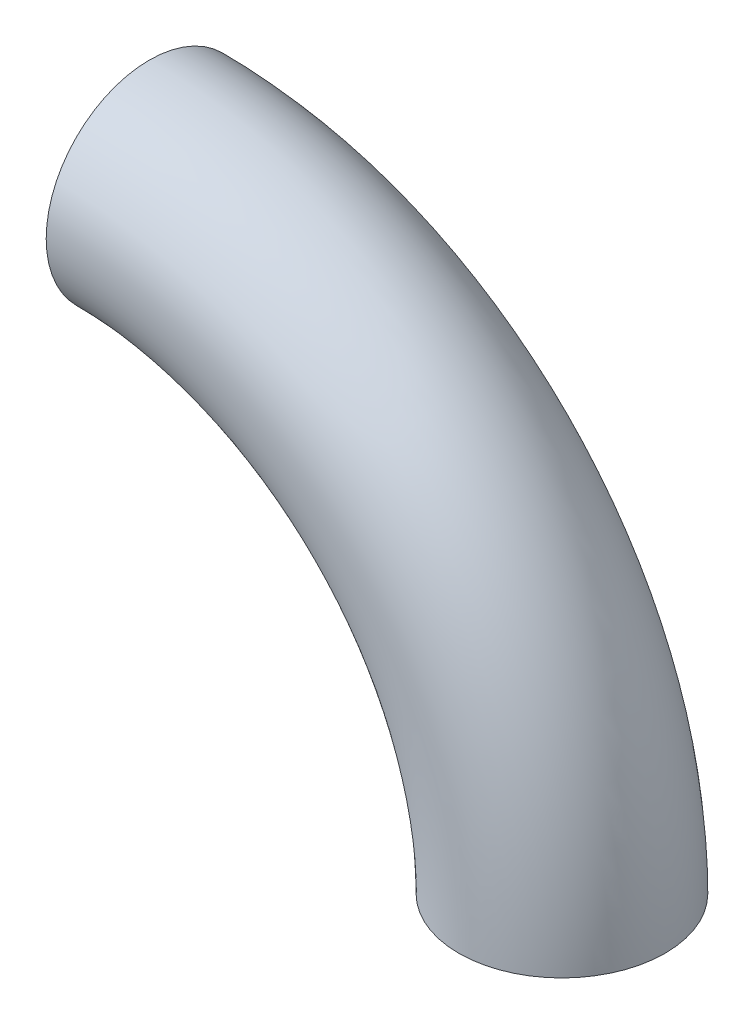
SolidWorks part; units mm, degrees
ref_plane "Front Plane" through (0, 0, 0) normal (0, 0, 1) x (1, 0, 0)
ref_plane "Top Plane" through (0, 0, 0) normal (0, 1, 0) x (1, 0, 0)
ref_plane "Right Plane" through (0, 0, 0) normal (1, 0, 0) x (0, 0, -1)
ref_plane "plane:profile-xz" through (0, 0, 0) normal (0, -1, 0) x (1, 0, 0)
sketch "sketch:main-profile" plane through (0, 0, 0) normal (0, -1, 0) x (1, 0, 0)
  line L0 (0, -15) -> (0, 15) construction
  circle A0 centre (20, 0) radius 5
revolve "feature:torus" add sketch "sketch:main-profile" angle 90 about L0
